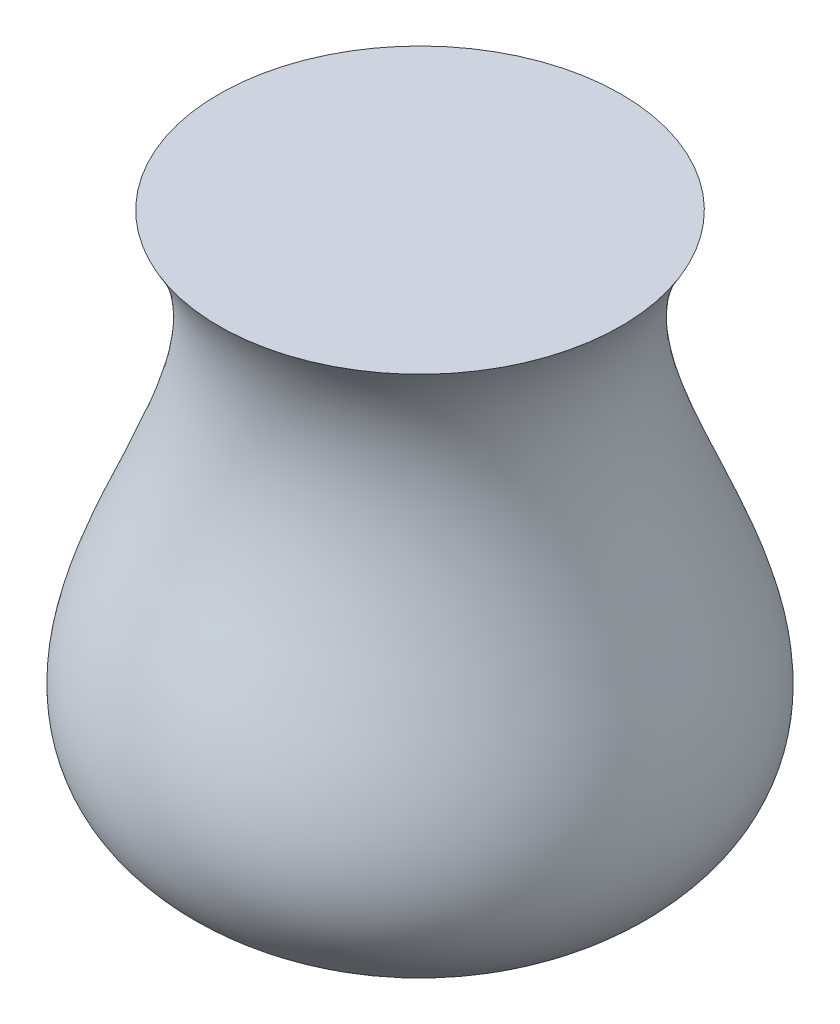
SolidWorks part; units mm, degrees
ref_plane "Front Plane" through (0, 0, 0) normal (0, 0, 1) x (1, 0, 0)
ref_plane "Top Plane" through (0, 0, 0) normal (0, 1, 0) x (1, 0, 0)
ref_plane "Right Plane" through (0, 0, 0) normal (1, 0, 0) x (0, 0, -1)
sketch "Çizim1" plane through (0, 0, 0) normal (0, 0, 1) x (1, 0, 0)
  line L2 (1, 0.9156) -> (66.4226, 0.9156)
  line L3 (1, 0.9156) -> (1, 266.3659)
  line L6 (1, 266.3659) -> (96.7003, 266.3659)
  spline S0 degree 3 poles (66.4226, 0.9156) (168.6828, 44.4171) (90.8481, 140.1569) (78.557, 238.1542) (96.7003, 266.3659) knots 0 0 0 0 0.62678 0.901321 0.901321 0.901321 0.901321
revolve "Döndür1" add sketch "Çizim1" angle 360 about L3
